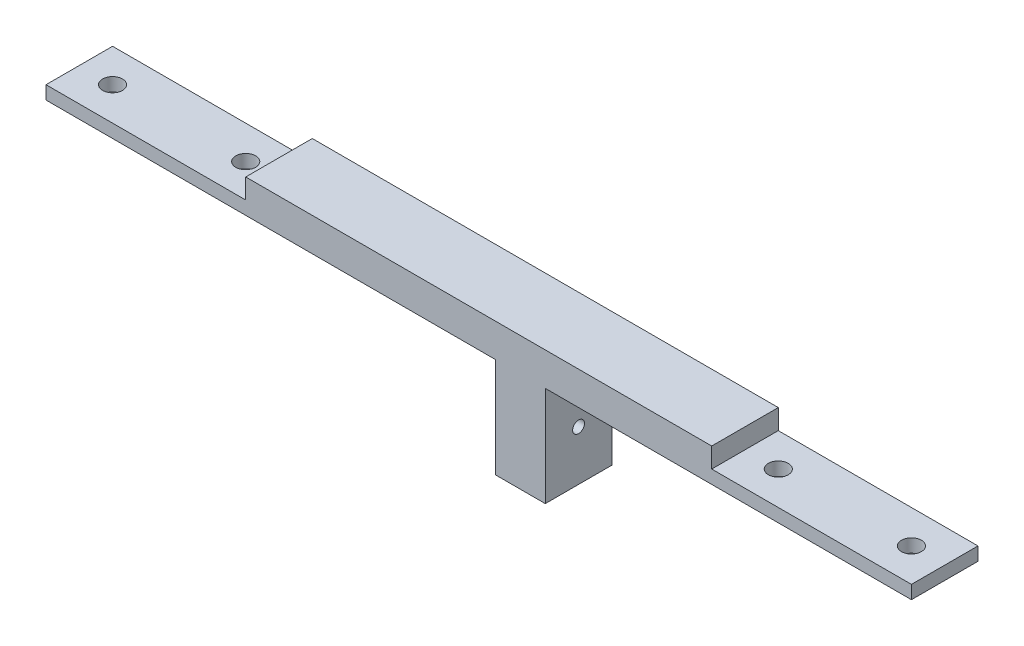
SolidWorks part; units mm, degrees
material "6061 Alloy"
ref_plane "Front Plane" through (0, 0, 0) normal (0, 0, 1) x (1, 0, 0)
ref_plane "Top Plane" through (0, 0, 0) normal (0, 1, 0) x (1, 0, 0)
ref_plane "Right Plane" through (0, 0, 0) normal (1, 0, 0) x (0, 0, -1)
sketch "Sketch1" plane through (0, 0, 0) normal (0, 1, 0) x (1, 0, 0)
  line L1 (-82.55, -6.35) -> (82.55, -6.35)
  line L2 (-82.55, -6.35) -> (-82.55, 6.35)
  line L3 (-82.55, 6.35) -> (82.55, 6.35)
  line L4 (82.55, -6.35) -> (82.55, 6.35)
  line L5 (-82.55, -6.35) -> (82.55, 6.35) construction
  line L6 (-82.55, 6.35) -> (82.55, -6.35) construction
  point P0 (0, 0)
  dimension "D1" = 12.7
  dimension "D2" = 165.1
extrude "Boss-Extrude1" add sketch "Sketch1" along normal blind 6.35 contours L1 L4 L3 L2
sketch "Sketch2" plane through (0, 0, 6.35) normal (0, 0, 1) x (1, 0, 0)
  line L1 (-82.55, 6.35) -> (-44.45, 6.35)
  line L2 (-82.55, 6.35) -> (-82.55, 2.54)
  line L3 (-82.55, 2.54) -> (-44.45, 2.54)
  line L4 (-44.45, 6.35) -> (-44.45, 2.54)
  dimension "D1" = 3.81
  dimension "D2" = 38.1
extrude "Cut-Extrude1" cut sketch "Sketch2" against normal through all contours L3 L4 L1 L2
hole_wizard "#6 Clearance Hole1" positions "Sketch5" profile "Sketch4" hole size "#6" standard "ANSI Inch" end condition through all
sketch "Sketch5" plane through (0, 0, 0) normal (0, -1, 0) x (-1, 0, 0)
  line L0 (82.55, -6.35) -> (82.55, 6.35) construction
  line L1 (82.55, -6.35) -> (-82.55, -6.35) construction
  point P0 (50.8, 0)
  point P2 (76.2, 0)
  dimension "D1" = 6.35
  dimension "D2" = 31.75
  dimension "D3" = 6.35
  dimension "D4" = 6.35
sketch "Sketch4" plane through (-50.8, 0, 0) normal (1, 0, 0) x (0, 0, -1)
  line L0 (0, 0) -> (0, 6.35)
  line L1 (0, 6.35) -> (1.8986, 6.35)
  line L2 (1.8986, 6.35) -> (1.8986, 0)
  line L5 (1.8986, 0) -> (0, 0)
  line L11 (0, -6.35) -> (0, 107.95) construction
  dimension "Thru Hole Dia." = 3.7973
  dimension "Thru Hole Depth" = 6.35
mirror "Mirror1" about plane through (0, 0, 0) normal (1, 0, 0) of "#6 Clearance Hole1", "Cut-Extrude1"
sketch "Sketch6" plane through (0, 0, 6.35) normal (0, 0, 1) x (1, 0, 0)
  line L0 (-82.55, 0) -> (82.55, 0) construction
  line L1 (3.175, 0) -> (12.7, 0)
  line L2 (3.175, 0) -> (3.175, -19.05)
  line L3 (3.175, -19.05) -> (12.7, -19.05)
  line L4 (12.7, 0) -> (12.7, -19.05)
  dimension "D1" = 9.525
  dimension "D2" = 12.7
  dimension "D3" = 19.05
extrude "Boss-Extrude2" add sketch "Sketch6" against normal up to surface (12.7 mm away) contours L3 L4 L1 L2 up to face at (0, 2.8575, -6.35)
hole_wizard "#4-40 Tapped Hole1" positions "Sketch7" profile "Sketch8" tap size "#4-40" standard "ANSI Inch" end condition through all
sketch "Sketch7" plane through (12.7, 0, 0) normal (1, 0, 0) x (0, 0, -1)
  line L0 (6.35, -19.05) -> (-6.35, -19.05) construction
  point P0 (0, -9.525)
  dimension "D1" = 9.525
sketch "Sketch8" plane through (12.7, -9.525, 0) normal (0, 1, 0) x (0, 0, -1)
  line L0 (0, 0) -> (0, 95.25)
  line L1 (0, 95.25) -> (1.1303, 95.25)
  line L2 (1.1303, 95.25) -> (1.1303, 0)
  line L5 (1.1303, 0) -> (0, 0)
  line L11 (0, -6.35) -> (0, 107.95) construction
  dimension "Thru Tap Drill Dia." = 2.2606
  dimension "Thru Tap Drill Depth" = 95.25
cosmetic thread "Hole Thread1"
